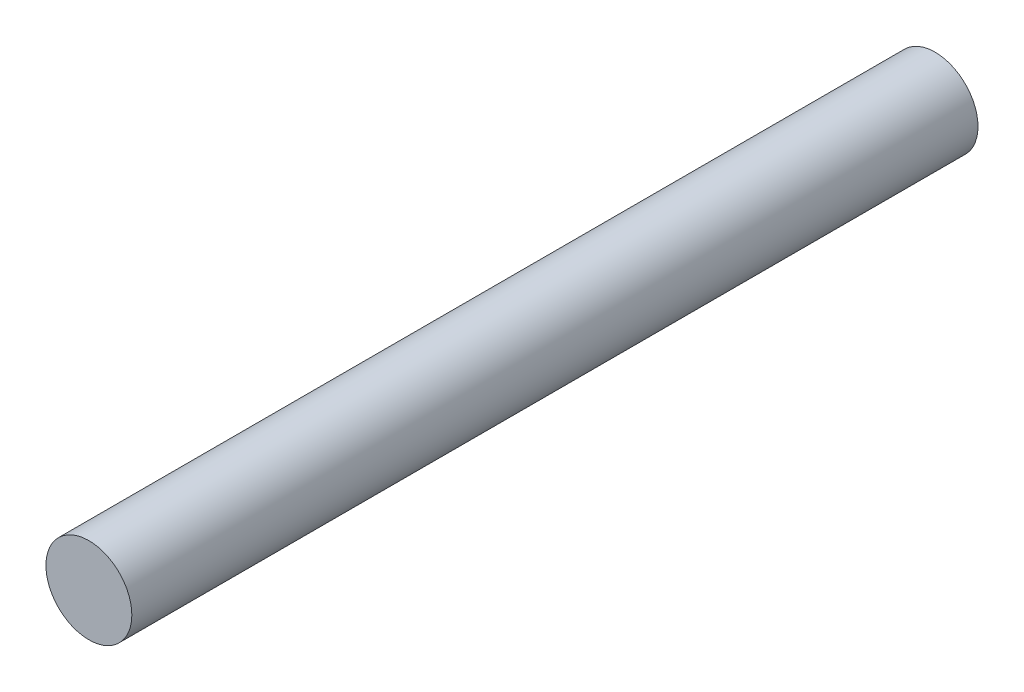
SolidWorks part; units mm, degrees
material "6061-T6 (SS)"
ref_plane "Front Plane" through (0, 0, 0) normal (0, 0, 1) x (1, 0, 0)
ref_plane "Top Plane" through (0, 0, 0) normal (0, 1, 0) x (1, 0, 0)
ref_plane "Right Plane" through (0, 0, 0) normal (1, 0, 0) x (0, 0, -1)
sketch "Sketch1" plane through (0, 0, 0) normal (0, 0, 1) x (1, 0, 0)
  circle A0 centre (0, 0) radius 4.7625
  dimension "D1" = 9.525
extrude "Boss-Extrude1" add sketch "Sketch1" along normal blind 93.8022
